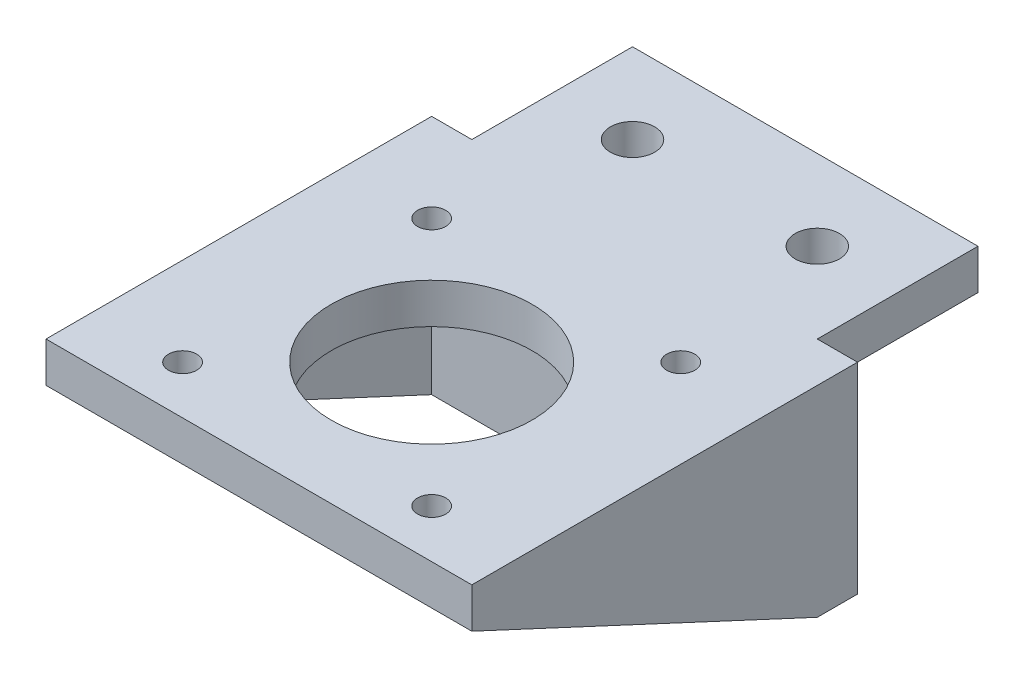
SolidWorks part; units mm, degrees
ref_plane "前视基准面" through (0, 0, 0) normal (0, 0, 1) x (1, 0, 0)
ref_plane "上视基准面" through (0, 0, 0) normal (0, 1, 0) x (1, 0, 0)
ref_plane "右视基准面" through (0, 0, 0) normal (1, 0, 0) x (0, 0, -1)
sketch "草图1" plane through (0, 0, 0) normal (0, 1, 0) x (1, 0, 0)
  line L1 (-15.1234, 10.3825) -> (27.8766, 10.3825)
  line L2 (-15.1234, 10.3825) -> (-15.1234, -32.6175)
  line L3 (-15.1234, -32.6175) -> (27.8766, -32.6175)
  line L4 (27.8766, 10.3825) -> (27.8766, -32.6175)
  line L5 (-15.1234, 10.3825) -> (27.8766, -32.6175) construction
  line L6 (-15.1234, -32.6175) -> (27.8766, 10.3825) construction
  line L11 (-9.1234, 4.3825) -> (21.8766, 4.3825) construction
  line L12 (-9.1234, 4.3825) -> (-9.1234, -26.6175) construction
  line L13 (-9.1234, -26.6175) -> (21.8766, -26.6175) construction
  line L14 (21.8766, 4.3825) -> (21.8766, -26.6175) construction
  line L15 (6.3766, -26.6175) -> (6.3766, 4.3825) construction
  line L16 (-9.1234, -11.1175) -> (21.8766, -11.1175) construction
  circle A5 centre (-9.1234, -26.6175) radius 1.75
  circle A6 centre (21.8766, -26.6175) radius 1.75
  circle A7 centre (21.8766, 4.3825) radius 1.75
  circle A8 centre (-9.1234, 4.3825) radius 1.75
  circle A9 centre (6.3766, -11.1175) radius 12.5
  point P4 (6.3766, -11.1175)
  point P5 (6.3766, -11.1175)
  point P6 (6.3766, -11.1175)
  dimension "D3" = 31
  dimension "D5" = 3.5
  dimension "D6" = 25
  dimension "D1" = 43
  dimension "D2" = 43
  dimension "D4" = 31
extrude "凸台-拉伸1" add sketch "草图1" along normal blind 5
sketch "草图2" plane through (0, 0, -10.3825) normal (0, 0, -1) x (-1, 0, 0)
  line L4 (-27.8766, 0) -> (15.1234, 0)
  line L5 (15.1234, 0) -> (15.1234, 5)
  line L6 (15.1234, 5) -> (-27.8766, 5)
  line L7 (-27.8766, 5) -> (-27.8766, 0)
  line L8 (-27.8766, 0) -> (15.1234, 0)
  line L9 (15.1234, 0) -> (15.1234, 5)
  line L10 (15.1234, 5) -> (-27.8766, 5)
  line L11 (-27.8766, 5) -> (-27.8766, 0)
  dimension "D1" = 0
extrude "凸台-拉伸2" add sketch "草图2" along normal blind 25
sketch "草图3" plane through (0, 0, 0) normal (0, -1, 0) x (1, 0, 0)
  line L0 (-15.1234, -35.3825) -> (-15.1234, 32.6175) construction
  line L1 (-15.1234, -10.3825) -> (27.8766, -10.3825)
  line L2 (-15.1234, -10.3825) -> (-15.1234, -15.3825)
  line L3 (-15.1234, -15.3825) -> (27.8766, -15.3825)
  line L4 (27.8766, -10.3825) -> (27.8766, -15.3825)
  line L5 (-15.1234, -10.3825) -> (27.8766, -15.3825) construction
  line L6 (-15.1234, -15.3825) -> (27.8766, -10.3825) construction
  line L7 (27.8766, 32.6175) -> (27.8766, -35.3825) construction
  line L8 (27.8766, -35.3825) -> (-15.1234, -35.3825) construction
  point P4 (6.3766, -12.8825)
  dimension "D1" = 20
  dimension "D2" = 5
extrude "凸台-拉伸3" add sketch "草图3" along normal blind 20
sketch "草图4" plane through (27.8766, 0, 0) normal (1, 0, 0) x (0, 0, -1)
  line L0 (-32.6175, 0) -> (10.3825, -20)
  line L1 (10.3825, -20) -> (15.3825, -20)
  line L2 (15.3825, -20) -> (15.3825, 5)
  line L3 (-32.6175, 5) -> (35.3825, 5) construction
  line L4 (15.3825, 5) -> (-32.6175, 5)
  line L5 (-32.6175, 5) -> (-32.6175, 0)
extrude "凸台-拉伸4" add sketch "草图4" along normal blind 5
sketch "草图7" plane through (0, 0, 0) normal (0, -1, 0) x (1, 0, 0)
  line L0 (-15.1234, 32.6175) -> (27.8766, 32.6175) construction
  line L1 (6.3766, 32.6175) -> (6.3766, -10.3825)
  line L2 (27.8766, -10.3825) -> (-15.1234, -10.3825) construction
sketch "草图9" plane through (-15.1234, 0, 0) normal (-1, 0, 0) x (0, 0, 1)
  line L0 (32.6175, 5) -> (32.6175, 0)
  line L5 (-10.3825, -20) -> (-15.3825, -20)
  line L6 (-15.3825, -20) -> (-15.3825, 5)
  line L7 (-35.3825, 5) -> (32.6175, 5) construction
  line L8 (-15.3825, 5) -> (32.6175, 5)
  line L10 (32.6175, 0) -> (-10.3825, -20)
extrude "凸台-拉伸6" add sketch "草图9" along normal blind 5
sketch "草图10" plane through (0, 5, 0) normal (0, 1, 0) x (1, 0, 0)
  line L0 (-15.1234, 25.3825) -> (27.8766, 25.3825) construction
  line L1 (-15.1234, 35.3825) -> (-15.1234, 15.3825) construction
  line L2 (27.8766, 15.3825) -> (27.8766, 35.3825) construction
  circle A0 centre (-5.1234, 25.3825) radius 2.75
  circle A1 centre (17.8766, 25.3825) radius 2.75
  dimension "D1" = 5.5
  dimension "D2" = 5.5
  dimension "D3" = 10
  dimension "D4" = 10
extrude "切除-拉伸1" cut sketch "草图10" against normal through all
